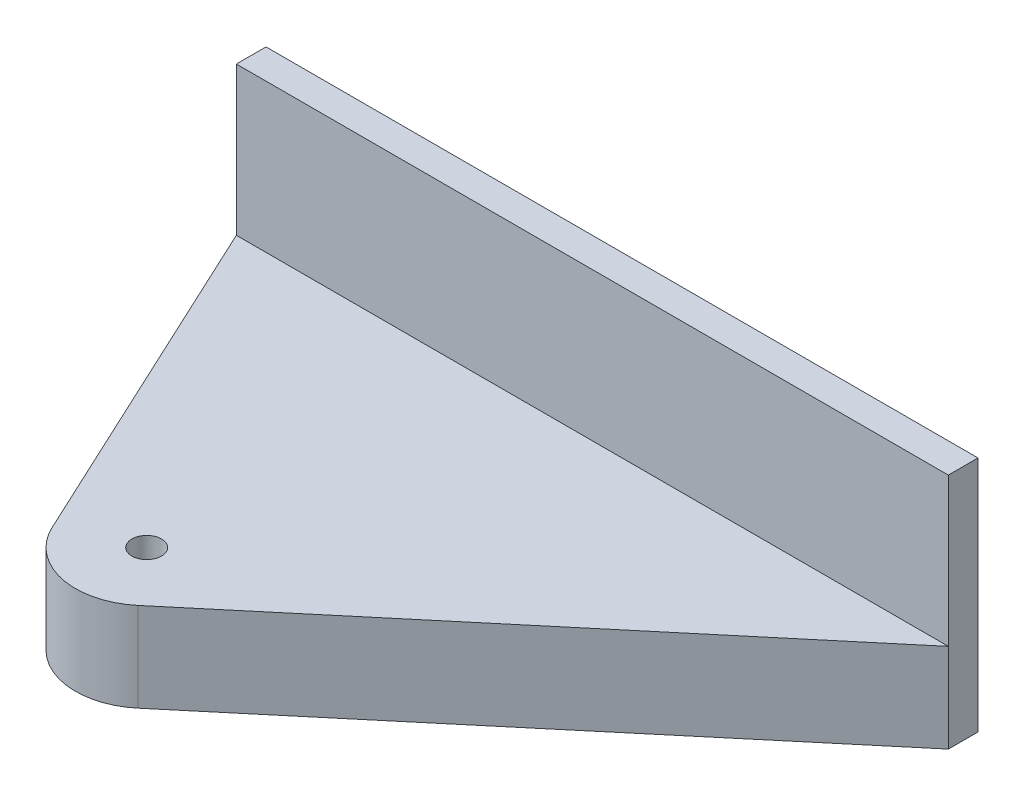
SolidWorks part; units mm, degrees
material "6061 Alloy"
ref_plane "Front" through (0, 0, 0) normal (0, 0, 1) x (1, 0, 0)
ref_plane "Top" through (0, 0, 0) normal (0, 1, 0) x (1, 0, 0)
ref_plane "Right" through (0, 0, 0) normal (1, 0, 0) x (0, 0, -1)
sketch "Sketch1" plane through (0, 0, 0) normal (0, 0, 1) x (1, 0, 0)
  line L1 (0, 0) -> (-76.2, 0)
  line L2 (0, 0) -> (0, 25.4)
  line L3 (0, 25.4) -> (-76.2, 25.4)
  line L4 (-76.2, 0) -> (-76.2, 25.4)
  dimension "D1" = 25.4
  dimension "D2" = 76.2
extrude "Boss-Extrude1" add sketch "Sketch1" along normal blind 3.175
sketch "Sketch2" plane through (0, 0, 0) normal (0, -1, 0) x (-1, 0, 0)
  line L0 (0, 0) -> (76.2, 0)
  line L1 (76.2, 0) -> (76.2, -3.175)
  line L2 (76.2, -3.175) -> (58.9666, -40.1321)
  line L3 (47.1625, -42.749) -> (0, -3.175)
  line L4 (0, -3.175) -> (0, 0)
  line L5 (76.2, -3.175) -> (0, -3.175) construction
  arc A0 (58.9666, -40.1321) -> (47.1625, -42.749) centre (52.0605, -36.9118) cw
  dimension "D1" = 65
  dimension "D3" = 7.62
  dimension "D2" = 40
extrude "Boss-Extrude2" add sketch "Sketch2" against normal blind 9.525
sketch "Sketch3" plane through (0, 9.525, 0) normal (0, 1, 0) x (1, 0, 0)
  circle A0 centre (-52.0605, -36.9118) radius 1.5875
  dimension "D1" = 3.175
extrude "Cut-Extrude1" cut sketch "Sketch3" against normal up to surface (9.525 mm away) and the other way through all up to face at (-43.1957, 0, 15.357)
